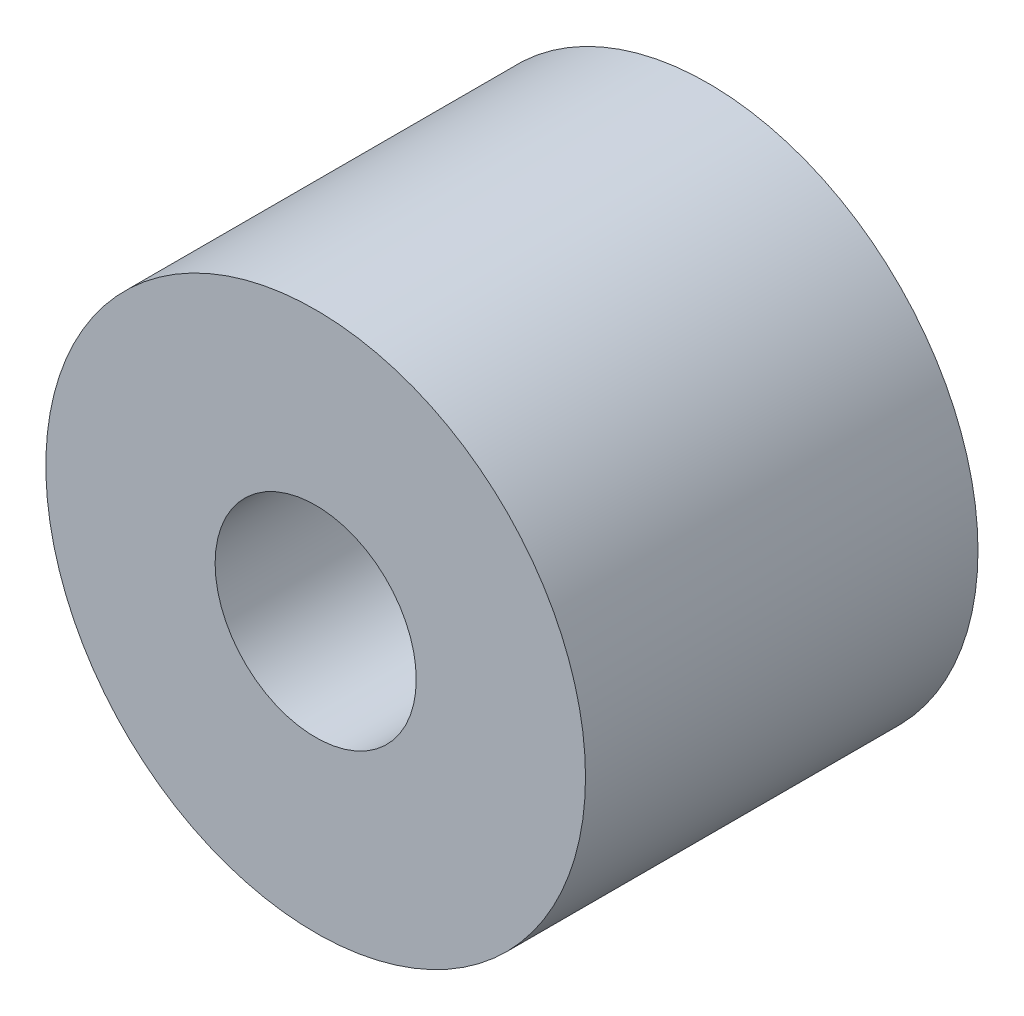
SolidWorks part; units mm, degrees
ref_plane "Front Plane" through (0, 0, 0) normal (0, 0, 1) x (1, 0, 0)
ref_plane "Top Plane" through (0, 0, 0) normal (0, 1, 0) x (1, 0, 0)
ref_plane "Right Plane" through (0, 0, 0) normal (1, 0, 0) x (0, 0, -1)
sketch "Sketch1" plane through (0, 0, 0) normal (0, 0, 1) x (1, 0, 0)
  circle A0 centre (0, 0) radius 5.5
  circle A1 centre (0, 0) radius 2.05
  dimension "D1" = 11
  dimension "D2" = 4.1
extrude "Boss-Extrude1" add sketch "Sketch1" along normal blind 8
